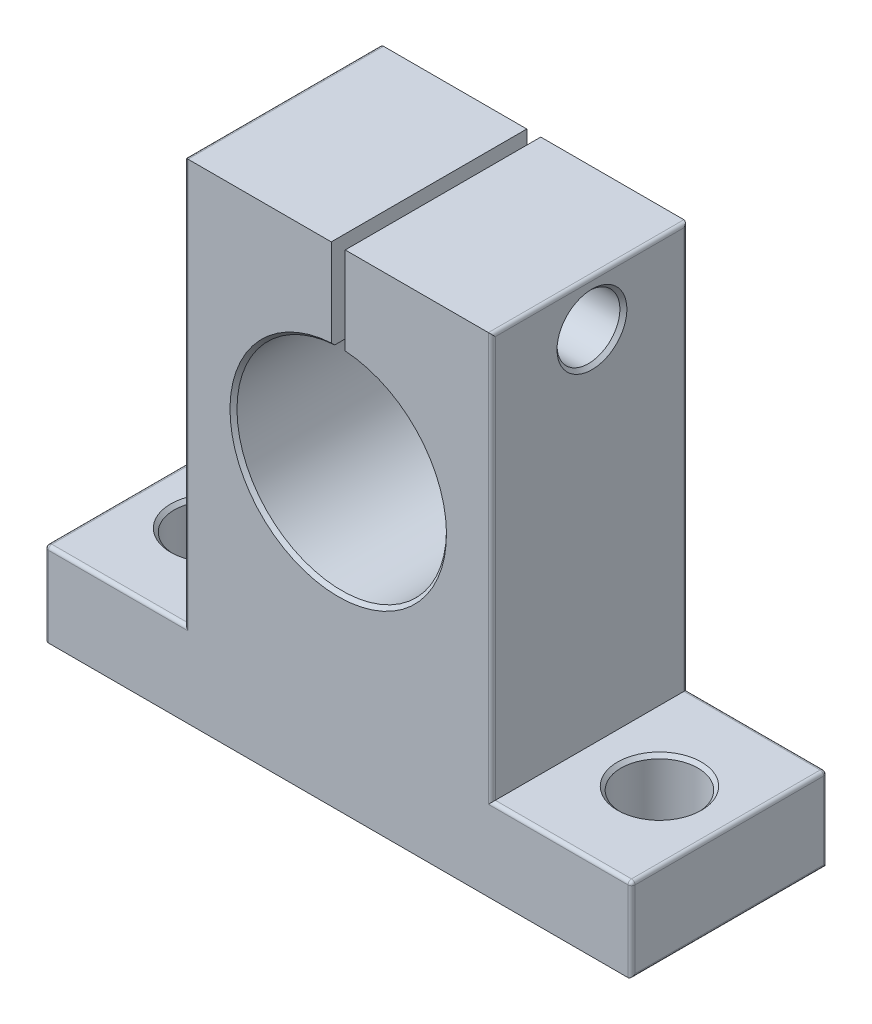
SolidWorks part; units mm, degrees
material "1060 Alloy"
ref_plane "Front Plane" through (0, 0, 0) normal (0, 0, 1) x (1, 0, 0)
ref_plane "Top Plane" through (0, 0, 0) normal (0, 1, 0) x (1, 0, 0)
ref_plane "Right Plane" through (0, 0, 0) normal (1, 0, 0) x (0, 0, -1)
sketch "Sketch1" plane through (0, 0, 0) normal (0, 0, 1) x (1, 0, 0)
  line L0 (0, 0) -> (-50000, 0) construction
  line L1 (0, 0) -> (0, 50000) construction
  line L2 (-42, -6) -> (-42, 6)
  line L3 (-42, 6) -> (-22, 6)
  line L4 (-22, 6) -> (-22, 64)
  line L5 (-22, 64) -> (-1, 64)
  line L6 (22, 64) -> (22, 6)
  line L7 (22, 6) -> (42, 6)
  line L8 (42, 6) -> (42, -6)
  line L9 (42, -6) -> (-42, -6)
  line L10 (32, -3) -> (32, 3) construction
  line L11 (-32, -3) -> (-32, 3) construction
  line L12 (-1, 64) -> (-1, 50.9666)
  line L13 (1, 64) -> (1, 50.9666)
  line L14 (1, 64) -> (22, 64)
  arc A0 (-1, 50.9666) -> (1, 50.9666) centre (0, 36) ccw
  point P8 (-42, 0)
  point P15 (0, -6)
  point P21 (32, 0)
  dimension "Shaft Diameter" = 30
  dimension "W" = 84
  dimension "P" = 44
  dimension "F" = 70
  dimension "G" = 12
  dimension "B" = 64
  dimension "D1" = 2
  dimension "h" = 42
extrude "Boss-Extrude1" add sketch "Sketch1" along normal mid plane 28
sketch "Sketch2" plane through (0, 6, 0) normal (0, 1, 0) x (1, 0, 0)
  line L0 (0, 0) -> (50000, 0) construction
  line L1 (0.3141, 0) -> (-49999.6859, 0) construction
  line L2 (0, 2.4842) -> (0, 50002.4842) construction
  circle A0 centre (32, 0) radius 5.5
  circle A1 centre (-32, 0) radius 5.5
  dimension "B" = 64
  dimension "S" = 11
extrude "Cut-Extrude1" cut sketch "Sketch2" against normal through all
sketch "Sketch5" plane through (-1, 0, 0) normal (1, 0, 0) x (0, 0, -1)
  line L0 (-14, 57.4833) -> (14, 57.4833) construction
  line L1 (14, 50.9666) -> (14, 64) construction
  line L2 (0, 64) -> (0, 50.9666) construction
  line L3 (-14, 64) -> (14, 64) construction
  line L4 (-14, 50.9666) -> (14, 50.9666) construction
  line L5 (-14, 50.9666) -> (-14, 64) construction
  circle A0 centre (0.3307, 57.4833) radius 4.5
  dimension "Clamping bold" = 9
extrude "Cut-Extrude2" cut sketch "Sketch5" against normal through all both and the other way through all
chamfer "Chamfer2" distance 0.5 angle 45 6 edges at (0, 21, -14) (0, 21, 14) (-22, 57.4833, -4.8307) (-26.5, 6, 0) (22, 57.4833, 4.1693) (26.5, 6, 0)
fillet "Fillet2" radius 0.5 18 edges at (42, -6, 0) (42, 0, 14) (42, 6, 0) (42, 0, -14) (-42, 6, 0) (-42, 0, 14) (-42, -6, 0) (-42, 0, -14) (-32, 6, -14) (-32, 6, 14) (-22, 35, 14) (-22, 64, 0) (-22, 35, -14) (22, 35, -14) (22, 35, 14) (32, 6, 14) (32, 6, -14) (22, 64, 0)
equation "\"W\"= \"W@Sketch1\"'Width"
equation "\"B\"= \"B@Sketch1\"'between hold"
equation "\"F\"= \"F@Sketch1\"'Hight"
equation "\"P\"= \"P@Sketch1\""
equation "\"G\"= \"G@Sketch1\""
equation "\"Shaft diameter\"= \"Shaft Diameter@Sketch1\""
equation "\"S\"= \"S@Sketch2\"'M10"
equation "\"Clamping bold\"= 9'M8"
equation "\"h\"= \"h@Sketch1\""
